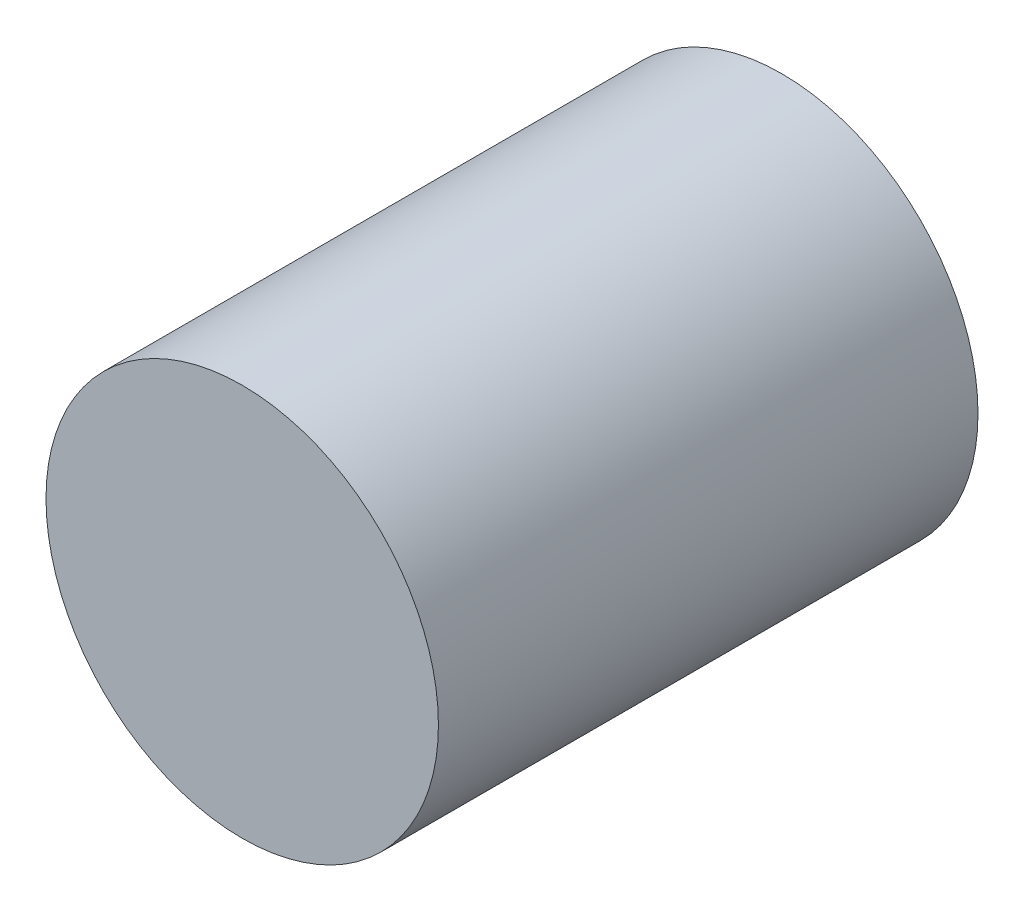
SolidWorks part; units mm, degrees
ref_plane "Front Plane" through (0, 0, 0) normal (1, 0, 0) x (0, 1, 0)
ref_plane "Top Plane" through (0, 0, 0) normal (0, 0, 1) x (0, 1, 0)
ref_plane "Right Plane" through (0, 0, 0) normal (0, 1, 0) x (-1, 0, 0)
sketch "Sketch1" plane through (0, 0, 0) normal (0, 0, 1) x (0, 1, 0)
  circle A0 centre (0, 0) radius 20
  dimension "D1" = 40
extrude "Boss-Extrude1" add sketch "Sketch1" along normal blind 55
